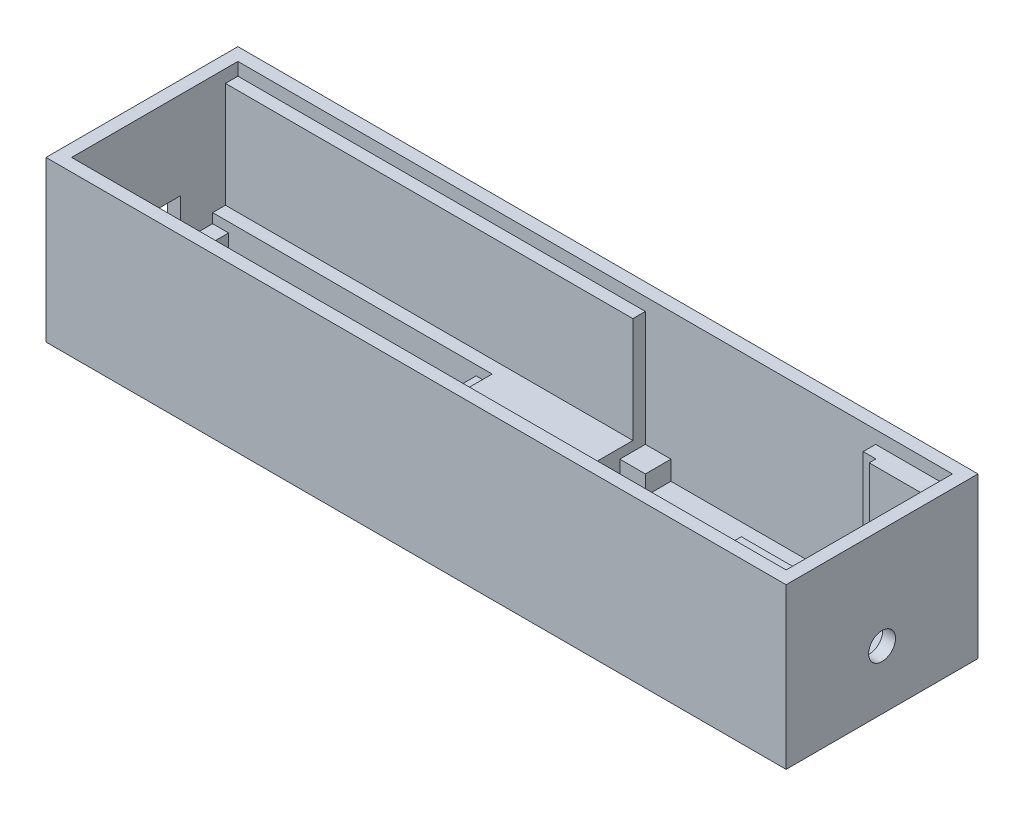
SolidWorks part; units mm, degrees
ref_plane "Plan de face" through (0, 0, 0) normal (0, 0, 1) x (1, 0, 0)
ref_plane "Plan de dessus" through (0, 0, 0) normal (0, 1, 0) x (1, 0, 0)
ref_plane "Plan de droite" through (0, 0, 0) normal (1, 0, 0) x (0, 0, -1)
sketch "Esquisse1" plane through (0, 0, 0) normal (0, 1, 0) x (1, 0, 0)
  line L0 (36, 13) -> (0, 13) construction
  line L1 (0, 0) -> (36, 0)
  line L2 (0, 0) -> (0, 26)
  line L3 (0, 26) -> (36, 26)
  line L4 (36, 0) -> (36, 26)
  line L9 (-63.7, 22.05) -> (-20, 22.05)
  line L10 (-63.7, 22.05) -> (-63.7, 3.95)
  line L11 (-63.7, 3.95) -> (-20, 3.95)
  line L12 (-20, 22.05) -> (-20, 3.95)
  line L13 (-20, 13) -> (-63.7, 13) construction
  line L14 (38, 13) -> (48, 13) construction
  line L15 (50, -2) -> (-65.7, -2)
  line L16 (50, -2) -> (50, 28)
  line L17 (50, 28) -> (-65.7, 28)
  line L18 (-65.7, -2) -> (-65.7, 28)
  line L19 (38, 23) -> (48, 23)
  line L20 (38, 23) -> (38, 3)
  line L21 (38, 3) -> (48, 3)
  line L22 (48, 23) -> (48, 3)
  dimension "D1" = 36
  dimension "D2" = 26
  dimension "D3" = 43.7
  dimension "D4" = 18.1
  dimension "D5" = 20
  dimension "D6" = 2
  dimension "D7" = 2
  dimension "D8" = 2
  dimension "D9" = 2
  dimension "D10" = 10
  dimension "D11" = 2
  dimension "D12" = 20
extrude "Boss.-Extru.1" add sketch "Esquisse1" along normal blind 21
sketch "Esquisse2" plane through (0, 0, 0) normal (0, -1, 0) x (-1, 0, 0)
  line L1 (65.7, -2) -> (-50, -2)
  line L2 (65.7, -2) -> (65.7, 28)
  line L3 (65.7, 28) -> (-50, 28)
  line L4 (-50, -2) -> (-50, 28)
extrude "Boss.-Extru.2" add sketch "Esquisse2" along normal blind 2
sketch "Esquisse3" plane through (0, 0, 0) normal (0, 1, 0) x (1, 0, 0)
  line L0 (-41.85, 22.05) -> (-41.85, 3.95) construction
  line L1 (-63.7, 22.05) -> (-61.2, 22.05)
  line L2 (-63.7, 22.05) -> (-63.7, 19.55)
  line L3 (-63.7, 19.55) -> (-61.2, 19.55)
  line L4 (-61.2, 22.05) -> (-61.2, 19.55)
  line L5 (-20, 22.05) -> (-63.7, 22.05) construction
  line L6 (-63.7, 3.95) -> (-20, 3.95) construction
  line L7 (-63.7, 13) -> (-20, 13) construction
  line L8 (-63.7, 22.05) -> (-63.7, 3.95) construction
  line L9 (-20, 3.95) -> (-20, 22.05) construction
  line L10 (-20, 19.55) -> (-22.5, 19.55)
  line L11 (-22.5, 22.05) -> (-22.5, 19.55)
  line L12 (-20, 22.05) -> (-22.5, 22.05)
  line L13 (-20, 22.05) -> (-20, 19.55)
  line L14 (-20, 3.95) -> (-20, 6.45)
  line L15 (-20, 3.95) -> (-22.5, 3.95)
  line L16 (-22.5, 3.95) -> (-22.5, 6.45)
  line L17 (-20, 6.45) -> (-22.5, 6.45)
  line L18 (-63.7, 6.45) -> (-61.2, 6.45)
  line L19 (-61.2, 3.95) -> (-61.2, 6.45)
  line L20 (-63.7, 3.95) -> (-61.2, 3.95)
  line L21 (-63.7, 3.95) -> (-63.7, 6.45)
  dimension "D1" = 2.5
extrude "Boss.-Extru.3" add sketch "Esquisse3" along normal blind 3
sketch "Esquisse4" plane through (0, 0, 0) normal (0, 1, 0) x (1, 0, 0)
  line L0 (18, 26) -> (18, 0) construction
  line L1 (0, 26) -> (4, 26)
  line L2 (0, 26) -> (0, 22)
  line L3 (0, 22) -> (4, 22)
  line L4 (4, 26) -> (4, 22)
  line L5 (36, 26) -> (0, 26) construction
  line L6 (0, 0) -> (36, 0) construction
  line L7 (0, 13) -> (36, 13) construction
  line L8 (0, 26) -> (0, 0) construction
  line L9 (36, 0) -> (36, 26) construction
  line L10 (36, 22) -> (32, 22)
  line L11 (32, 26) -> (32, 22)
  line L12 (36, 26) -> (32, 26)
  line L13 (36, 26) -> (36, 22)
  line L14 (36, 0) -> (36, 4)
  line L15 (36, 0) -> (32, 0)
  line L16 (32, 0) -> (32, 4)
  line L17 (36, 4) -> (32, 4)
  line L18 (0, 4) -> (4, 4)
  line L19 (4, 0) -> (4, 4)
  line L20 (0, 0) -> (4, 0)
  line L21 (0, 0) -> (0, 4)
  dimension "D1" = 4
extrude "Boss.-Extru.4" add sketch "Esquisse4" along normal blind 3
sketch "Esquisse5" plane through (-63.7, 0, 0) normal (1, 0, 0) x (0, 0, -1)
  line L0 (3.95, 3) -> (6.45, 3) construction
  line L1 (9, 9.3) -> (17, 9.3)
  line L2 (9, 9.3) -> (9, 5.1)
  line L3 (9, 5.1) -> (17, 5.1)
  line L4 (17, 9.3) -> (17, 5.1)
  line L5 (13, 21) -> (13, -2) construction
  line L6 (22.05, 21) -> (3.95, 21) construction
  line L7 (-2, -2) -> (28, -2) construction
  point P12 (13, 9.3)
  dimension "D1" = 2.1
  dimension "D2" = 8
  dimension "D3" = 4.2
extrude "Enlèv. mat.-Extru.1" cut sketch "Esquisse5" against normal up to surface (2 mm away) up to face at (-65.7, 9.5, -13)
ref_plane "Plan5" through (0, 4.5, 0) normal (0, 1, 0) x (1, 0, 0)
sketch "Esquisse7" plane through (0, 4.5, 0) normal (0, 1, 0) x (1, 0, 0)
  line L0 (-63.7, 22.05) -> (-63.7, 3.95) construction
  line L1 (-63.7, 24.05) -> (38, 24.05)
  line L2 (-63.7, 24.05) -> (-63.7, 1.95)
  line L3 (-63.7, 1.95) -> (38, 1.95)
  line L4 (38, 24.05) -> (38, 1.95)
  line L6 (-20, 22.05) -> (-63.7, 22.05) construction
  line L7 (-63.7, 3.95) -> (-20, 3.95) construction
  line L8 (38, 23) -> (38, 3) construction
  dimension "D1" = 2
  dimension "D2" = 2
extrude "Enlèv. mat.-Extru.2" cut sketch "Esquisse7" along normal up to surface (16.5 mm away) up to face at (-7.85, 21, -13)
sketch "Esquisse8" plane through (48, 0, 0) normal (-1, 0, 0) x (0, 0, 1)
  line L0 (-13, 9.3) -> (-13, 5.1) construction
  line L1 (-9, 9.3) -> (-17, 9.3) construction
  line L2 (-17, 5.1) -> (-9, 5.1) construction
  line L3 (-17, 7.2) -> (-9, 7.2) construction
  line L4 (-17, 9.3) -> (-17, 5.1) construction
  line L5 (-9, 5.1) -> (-9, 9.3) construction
  circle A0 centre (-13, 7.2) radius 2.1
  point P14 (0, 0)
  point P15 (0, 0)
extrude "Enlèv. mat.-Extru.3" cut sketch "Esquisse8" against normal up to surface (2 mm away) up to face at (50, 9.5, -13)
sketch "Esquisse9" plane through (0, 21, 0) normal (0, 1, 0) x (1, 0, 0)
  line L1 (-65.7, 28) -> (50, 28)
  line L2 (-65.7, 28) -> (-65.7, -2)
  line L3 (-65.7, -2) -> (50, -2)
  line L4 (50, 28) -> (50, -2)
  line L5 (-63.7, 26) -> (48, 26)
  line L6 (-63.7, 26) -> (-63.7, 0)
  line L7 (-63.7, 0) -> (48, 0)
  line L8 (48, 26) -> (48, 0)
  dimension "D1" = 2
  dimension "D2" = 2
  dimension "D3" = 2
  dimension "D4" = 2
extrude "Boss.-Extru.5" add sketch "Esquisse9" along normal blind 2
